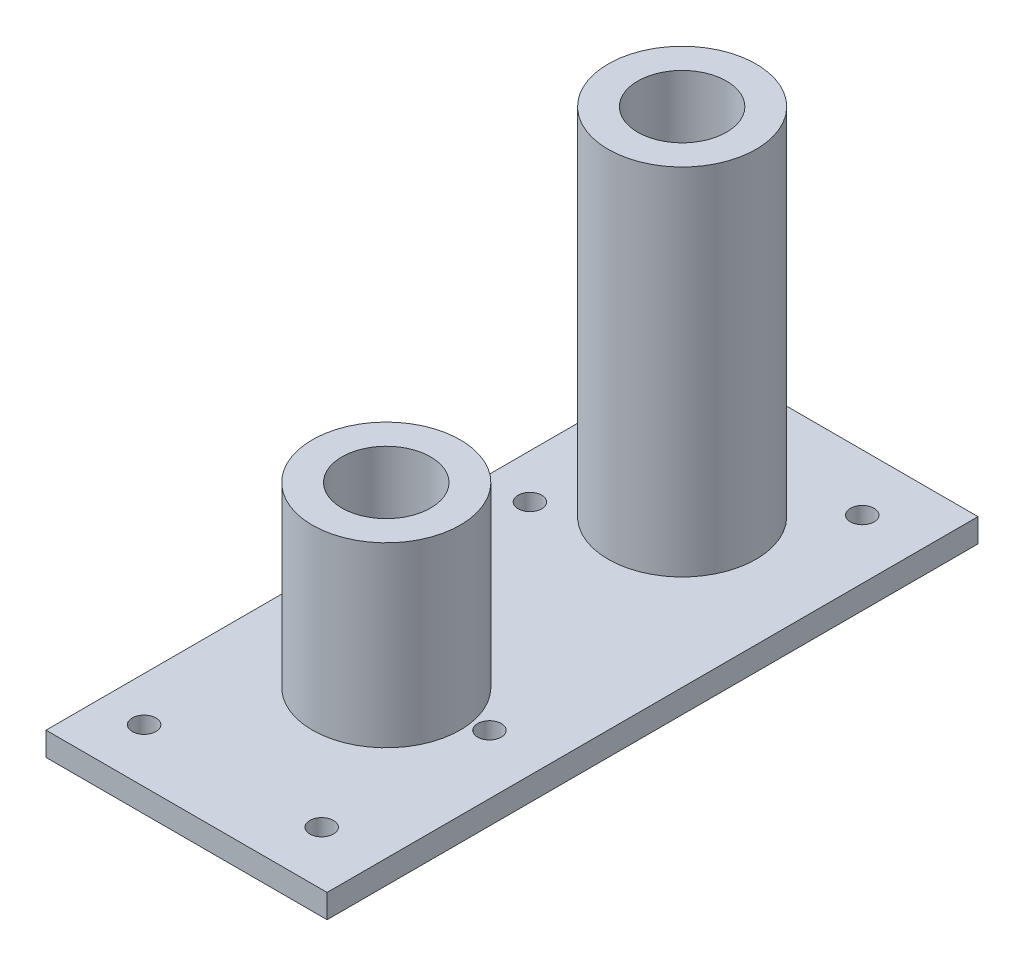
SolidWorks part; units mm, degrees
ref_plane "Płaszczyzna przednia" through (0, 0, 0) normal (0, 0, 1) x (1, 0, 0)
ref_plane "Płaszczyzna górna" through (0, 0, 0) normal (0, 1, 0) x (1, 0, 0)
ref_plane "Płaszczyzna prawa" through (0, 0, 0) normal (1, 0, 0) x (0, 0, -1)
sketch "Sketch1" plane through (0, 0, 0) normal (0, 1, 0) x (1, 0, 0)
  line L1 (-19.1477, 6.875) -> (-9.1477, 6.875)
  line L2 (-19.1477, 6.875) -> (-19.1477, -3.125)
  line L3 (-19.1477, -3.125) -> (-9.1477, -3.125)
  line L4 (-9.1477, 6.875) -> (-9.1477, -3.125)
  line L5 (-19.1477, 6.875) -> (-9.1477, -3.125) construction
  line L6 (-19.1477, -3.125) -> (-9.1477, 6.875) construction
  line L7 (-19.1477, -43.125) -> (-9.1477, -43.125)
  line L8 (-19.1477, -43.125) -> (-19.1477, -53.125)
  line L9 (-19.1477, -53.125) -> (-9.1477, -53.125)
  line L10 (-9.1477, -43.125) -> (-9.1477, -53.125)
  line L11 (-19.1477, -43.125) -> (-9.1477, -53.125) construction
  line L12 (-19.1477, -53.125) -> (-9.1477, -43.125) construction
  line L13 (-36.6477, 26.875) -> (10.8523, 26.875)
  line L14 (-36.6477, 26.875) -> (-36.6477, -83.125)
  line L15 (-36.6477, -83.125) -> (10.8523, -83.125)
  line L16 (10.8523, 26.875) -> (10.8523, -83.125)
  circle A0 centre (0.8523, 17.315) radius 2
  circle A1 centre (-29.1477, -8.845) radius 2
  circle A2 centre (0.8523, -45.685) radius 2
  circle A3 centre (0.8523, -74.045) radius 2
  circle A4 centre (-29.1477, -74.045) radius 2
  point P0 (-14.6023, 1.875)
  point P5 (-2.5568, 5.0568)
  dimension "D3" = 4
  dimension "D4" = 4
  dimension "D5" = 4
  dimension "D6" = 4
  dimension "D7" = 4
  dimension "D1" = 10
  dimension "D2" = 40
  dimension "D8" = 10
  dimension "D9" = 10.44
  dimension "D10" = 15.72
  dimension "D11" = 10
  dimension "D12" = 30.92
  dimension "D13" = 10
  dimension "D14" = 10
  dimension "D15" = 20.92
  dimension "D16" = 2.56
  dimension "D17" = 10
  dimension "D18" = 20
  dimension "D19" = 17.5
  dimension "D20" = 20
  dimension "D21" = 30
extrude "Boss-Extrude1" add sketch "Sketch1" against normal blind 4
sketch "Sketch2" plane through (0, 0, 0) normal (0, 1, 0) x (1, 0, 0)
  line L0 (-19.1477, -3.125) -> (-9.1477, 6.875) construction
  line L1 (-19.1477, -53.125) -> (-9.1477, -43.125) construction
  circle A2 centre (-14.1477, -48.125) radius 12.5
  circle A3 centre (-14.1477, -48.125) radius 7.5
  point P5 (-14.1477, 1.875)
  dimension "D3" = 2
extrude "Boss-Extrude2" add sketch "Sketch2" along normal blind 30 contours A2 | A3
sketch "Sketch4" plane through (0, 0, 0) normal (0, 1, 0) x (1, 0, 0)
  line L0 (-19.1477, 6.875) -> (-9.1477, -3.125) construction
  circle A0 centre (-14.1477, 1.875) radius 12.5
  circle A1 centre (-14.1477, 1.875) radius 7.5
  point P7 (-14.1477, 1.875)
  dimension "D1" = 15
  dimension "D2" = 25
extrude "Boss-Extrude3" add sketch "Sketch4" along normal blind 60
